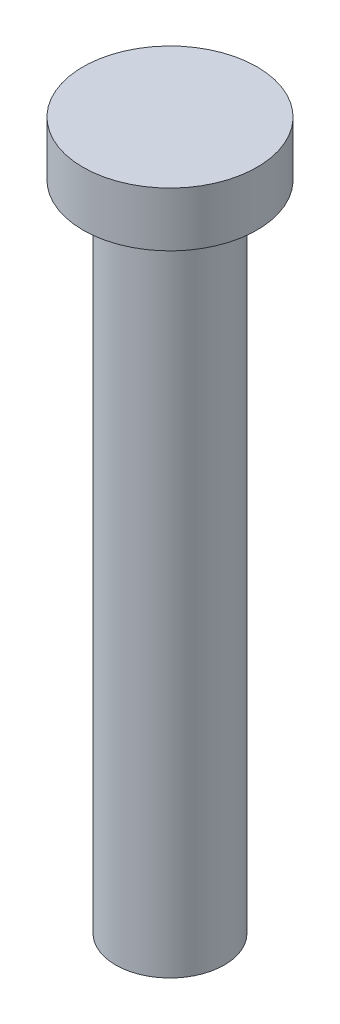
SolidWorks part; units mm, degrees
ref_plane "Front Plane" through (0, 0, 0) normal (0, 0, 1) x (1, 0, 0)
ref_plane "Top Plane" through (0, 0, 0) normal (0, 1, 0) x (1, 0, 0)
ref_plane "Right Plane" through (0, 0, 0) normal (1, 0, 0) x (0, 0, -1)
sketch "Sketch1" plane through (0, 0, 0) normal (0, 1, 0) x (1, 0, 0)
  circle A0 centre (0, 0) radius 2.5
extrude "Boss-Extrude1" add sketch "Sketch1" along normal blind 30
sketch "Sketch2" plane through (0, 30, 0) normal (0, 1, 0) x (1, 0, 0)
  circle A0 centre (0, 0) radius 4
  dimension "D1" = 8
extrude "Boss-Extrude2" add sketch "Sketch2" along normal blind 2.5
chamfer "Chamfer1" distance 1 angle 45 1 edges at (0, 30, 2.5)
